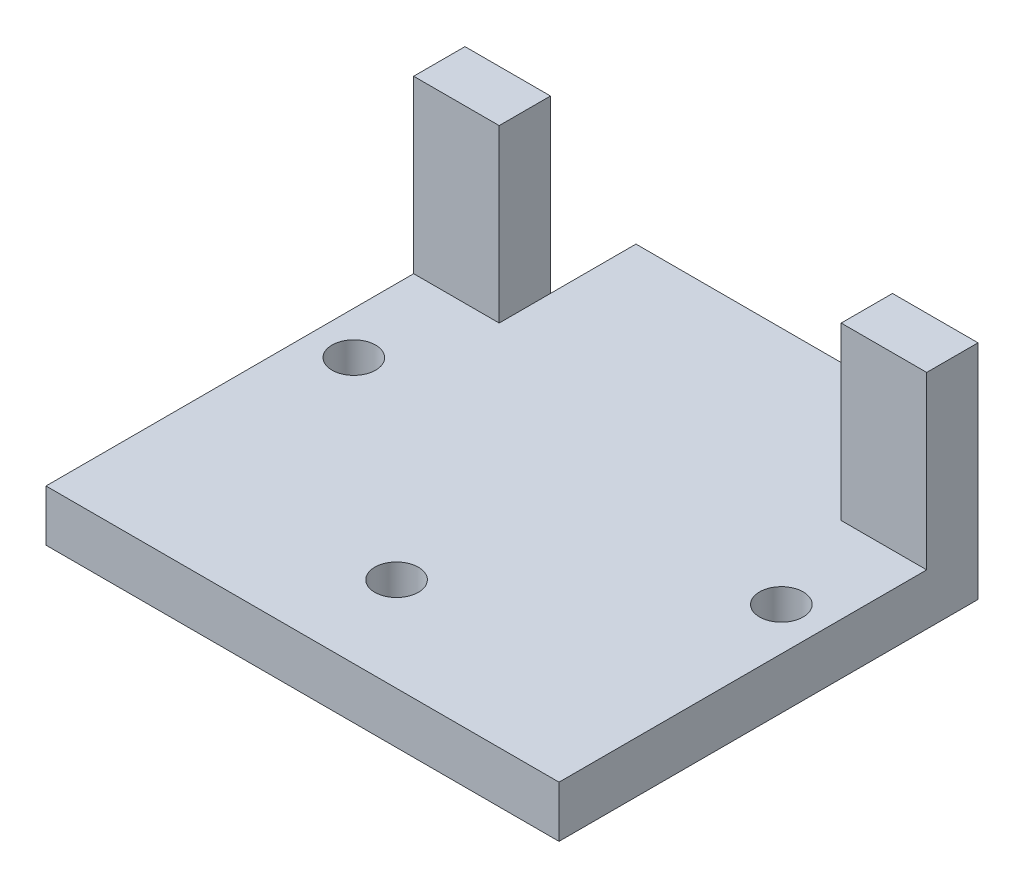
SolidWorks part; units mm, degrees
ref_plane "Front Plane" through (0, 0, 0) normal (0, 0, 1) x (1, 0, 0)
ref_plane "Top Plane" through (0, 0, 0) normal (0, 1, 0) x (1, 0, 0)
ref_plane "Right Plane" through (0, 0, 0) normal (1, 0, 0) x (0, 0, -1)
sketch "Sketch1" plane through (0, 0, 0) normal (0, 1, 0) x (1, 0, 0)
  line L1 (-30, -40) -> (30, -40)
  line L2 (-30, -40) -> (-30, 40)
  line L3 (-30, 40) -> (30, 40)
  line L4 (30, -40) -> (30, 40)
  line L5 (-30, -40) -> (30, 40) construction
  line L6 (-30, 40) -> (30, -40) construction
  point P0 (0, 0)
  dimension "D1" = 60
  dimension "D2" = 80
extrude "Boss-Extrude1" add sketch "Sketch1" along normal blind 6
sketch "Sketch2" plane through (0, 6, 0) normal (0, 1, 0) x (1, 0, 0)
  line L0 (-30, 9) -> (30, 9) construction
  line L1 (-20, -19) -> (20, -19) construction
  line L2 (-20, -19) -> (-20, 19) construction
  line L3 (-20, 19) -> (20, 19) construction
  line L4 (20, -19) -> (20, 19) construction
  line L5 (-20, -19) -> (20, 19) construction
  line L6 (-20, 19) -> (20, -19) construction
  line L7 (-30, 40) -> (-30, -40) construction
  line L8 (30, -40) -> (30, 40) construction
  line L9 (-38.8916, 9) -> (-20, 9)
  line L10 (-20, 9) -> (-20, 19)
  line L11 (-20, 19) -> (20, 19)
  line L12 (20, 9) -> (20, 19)
  line L13 (-30, -40) -> (30, -40) construction
  line L16 (20, 9) -> (37.9451, 9)
  line L17 (37.9451, 9) -> (37.9451, 57.3367)
  line L18 (37.9451, 57.3367) -> (-38.8916, 57.3367)
  line L19 (-38.8916, 57.3367) -> (-38.8916, 9)
  circle A0 centre (25, -9) radius 2.55
  circle A1 centre (-25, -9) radius 2.55
  circle A2 centre (0, -29) radius 2.55
  point P0 (0, 0)
  point P23 (0, -40)
  dimension "D5" = 5
  dimension "D7" = 5.1
  dimension "D8" = 10
  dimension "D1" = 38
  dimension "D2" = 40
  dimension "D3" = 10
  dimension "D4" = 10
  dimension "D6" = 5
  dimension "D9" = 10
extrude "Cut-Extrude1" cut sketch "Sketch2" against normal through all
sketch "Sketch3" plane through (0, 6, 0) normal (0, 1, 0) x (1, 0, 0)
  line L0 (-30, 9) -> (-30, -40) construction
  line L1 (30, 3) -> (20, 3)
  line L2 (30, 3) -> (30, 9)
  line L3 (30, 9) -> (20, 9)
  line L4 (20, 3) -> (20, 9)
  line L5 (30, 3) -> (20, 9) construction
  line L6 (30, 9) -> (20, 3) construction
  line L7 (-30, 3) -> (-20, 3)
  line L8 (-30, 3) -> (-30, 9)
  line L9 (-30, 9) -> (-20, 9)
  line L10 (-20, 3) -> (-20, 9)
  line L11 (-30, 3) -> (-20, 9) construction
  line L12 (-30, 9) -> (-20, 3) construction
  line L13 (30, -40) -> (30, 9) construction
  point P0 (25, 6)
  point P6 (-25, 6)
  dimension "D1" = 6
  dimension "D2" = 6
extrude "Boss-Extrude2" add sketch "Sketch3" along normal blind 20
